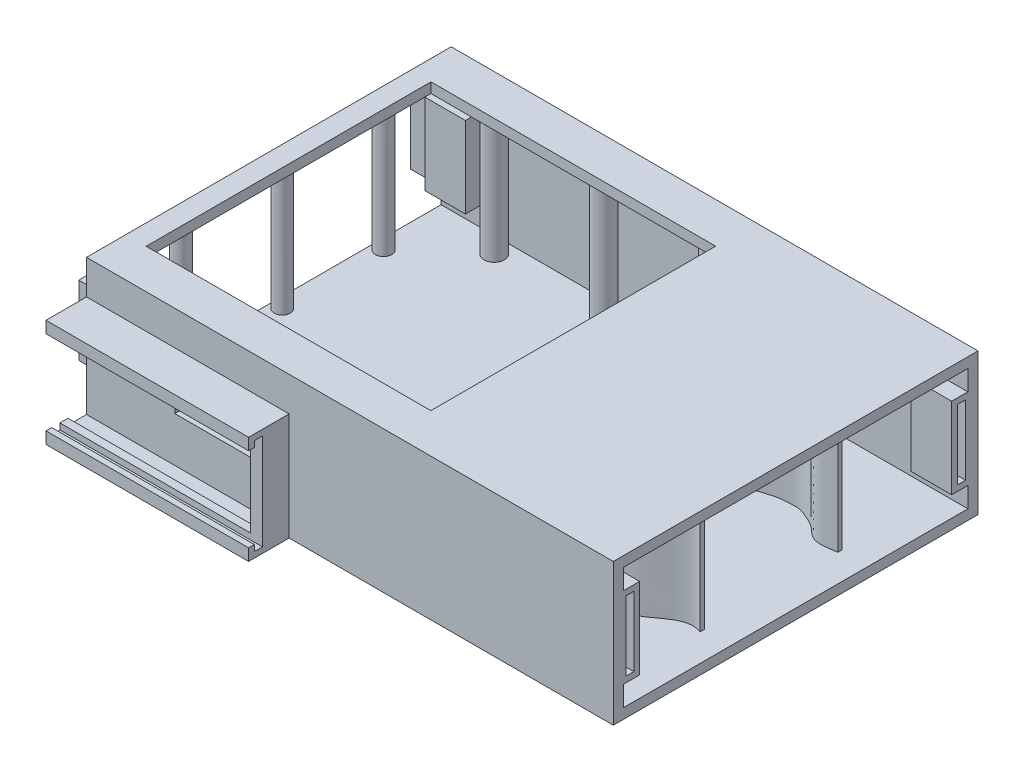
SolidWorks part; units mm, degrees
ref_plane "Спереди" through (0, 0, 0) normal (0, 0, 1) x (1, 0, 0)
ref_plane "Сверху" through (0, 0, 0) normal (0, 1, 0) x (1, 0, 0)
ref_plane "Справа" through (0, 0, 0) normal (1, 0, 0) x (0, 0, -1)
sketch "Эскиз1" plane through (0, 0, 0) normal (0, 1, 0) x (1, 0, 0)
  line L1 (-94.2008, -43.9132) -> (35.7992, -43.9132)
  line L2 (-94.2008, -43.9132) -> (-94.2008, 46.0868)
  line L3 (-94.2008, 46.0868) -> (35.7992, 46.0868)
  line L4 (35.7992, -43.9132) -> (35.7992, 46.0868)
  point P0 (0, 0)
extrude "Бобышка-Вытянуть1" add sketch "Эскиз1" along normal blind 35
sketch "Эскиз2" plane through (-94.2008, 0, 0) normal (-1, 0, 0) x (0, 0, 1)
  line L0 (-1046.0868, 17.5) -> (48953.9132, 17.5) construction
  line L1 (-46.0868, 35) -> (-46.0868, 0) construction
  line L2 (-1.0868, -965) -> (-1.0868, 49035) construction
  line L3 (-46.0868, 35) -> (43.9132, 35) construction
  line L5 (-43.5868, 2.5) -> (41.4132, 2.5)
  line L6 (-43.5868, 2.5) -> (-43.5868, 32.5)
  line L7 (-43.5868, 32.5) -> (41.4132, 32.5)
  line L8 (41.4132, 2.5) -> (41.4132, 32.5)
  line L9 (-43.5868, 2.5) -> (41.4132, 32.5) construction
  line L10 (-43.5868, 32.5) -> (41.4132, 2.5) construction
  point P5 (-46.0868, 17.5)
  point P6 (-1.0868, 17.5)
  point P10 (-1.0868, 35)
extrude "Вырез-Вытянуть1" cut sketch "Эскиз2" against normal through all
sketch "Эскиз3" plane through (-94.2008, 0, 0) normal (-1, 0, 0) x (0, 0, 1)
  line L0 (-43.5868, 27.5) -> (-43.5868, 7.5)
  line L1 (-43.5868, 32.5) -> (-43.5868, 2.5) construction
  line L2 (37.4132, 27.5) -> (37.4132, 7.5)
  line L3 (-43.5868, 7.5) -> (-39.5868, 7.5)
  line L4 (-39.5868, 7.5) -> (-39.5868, 27.5)
  line L5 (-39.5868, 27.5) -> (-43.5868, 27.5)
  line L6 (37.4132, 7.5) -> (41.4132, 7.5)
  line L7 (41.4132, 7.5) -> (41.4132, 27.5)
  line L8 (41.4132, 27.5) -> (37.4132, 27.5)
  dimension "D1" = 2
extrude "Бобышка-Вытянуть2" add sketch "Эскиз3" against normal blind 10
sketch "Эскиз4" plane through (-94.2008, 0, 0) normal (-1, 0, 0) x (0, 0, 1)
  line L6 (-41.0011, 8.9142) -> (-41.0011, 26.0858)
  line L7 (38.8274, 8.9142) -> (38.8274, 26.0858)
  line L8 (-41.0011, 26.0858) -> (-43.0011, 26.0858)
  line L9 (38.8274, 26.0858) -> (40.8274, 26.0858)
  line L10 (-43.0011, 26.0858) -> (-43.0011, 8.9142)
  line L11 (40.8274, 26.0858) -> (40.8274, 8.9142)
  line L12 (-43.0011, 8.9142) -> (-41.0011, 8.9142)
  line L13 (40.8274, 8.9142) -> (38.8274, 8.9142)
extrude "Бобышка-Вытянуть3" add sketch "Эскиз4" along normal blind 5
sketch "Эскиз5" plane through (0, 0, 43.9132) normal (0, 0, 1) x (1, 0, 0)
  line L3 (-72.421, 12.5) -> (-52.421, 12.5)
  line L4 (-72.421, 12.5) -> (-72.421, 22.5)
  line L5 (-72.421, 22.5) -> (-52.421, 22.5)
  line L6 (-52.421, 12.5) -> (-52.421, 22.5)
  line L7 (-72.421, 12.5) -> (-52.421, 22.5) construction
  line L8 (-72.421, 22.5) -> (-52.421, 12.5) construction
  point P1 (-62.421, 17.5)
extrude "Вырез-Вытянуть2" cut sketch "Эскиз5" against normal blind 5
sketch "Эскиз6" plane through (-94.2008, 0, 0) normal (-1, 0, 0) x (0, 0, 1)
  line L1 (43.9132, 35) -> (43.9132, 0) construction
  line L2 (43.9132, 26.54) -> (53.9132, 26.54)
  line L3 (53.9132, 26.54) -> (53.9132, 0)
  line L4 (53.9132, 0) -> (43.9132, 0)
  line L5 (43.9132, 0) -> (43.9132, 26.54)
extrude "Бобышка-Вытянуть4" add sketch "Эскиз6" against normal blind 50
sketch "Эскиз7" plane through (-94.2008, 0, 0) normal (-1, 0, 0) x (0, 0, 1)
  line L2 (52.4989, 25.1258) -> (52.4989, 1.4142)
  line L4 (52.4989, 25.1258) -> (43.9132, 25.1258)
  line L5 (43.9132, 25.1258) -> (43.9132, 1.4142)
  line L6 (43.9132, 1.4142) -> (52.4989, 1.4142)
extrude "Вырез-Вытянуть3" cut sketch "Эскиз7" against normal blind 47
sketch "Эскиз8" plane through (-94.2008, 0, 0) normal (-1, 0, 0) x (0, 0, 1)
  line L1 (53.9132, 0) -> (53.9132, 26.54) construction
  line L3 (53.9132, 2.91) -> (51.6765, 2.91)
  line L4 (51.6765, 2.91) -> (51.6765, 23.66)
  line L5 (51.6765, 23.66) -> (58.0156, 23.66)
  line L6 (58.0156, 23.66) -> (58.0156, 2.91)
  line L7 (58.0156, 2.91) -> (53.9132, 2.91)
extrude "Вырез-Вытянуть4" cut sketch "Эскиз8" against normal through all
sketch "Эскиз9" plane through (-94.2008, 0, 0) normal (-1, 0, 0) x (0, 0, 1)
  line L1 (52.4989, 25.1258) -> (43.9132, 25.1258) construction
  line L2 (43.9132, 1.4142) -> (52.4989, 1.4142) construction
  line L3 (50.4989, 25.1258) -> (50.4989, 23.66)
  line L4 (50.4989, 23.66) -> (48.5003, 23.66)
  line L5 (48.5003, 23.66) -> (48.5003, 25.1258)
  line L6 (48.5003, 25.1258) -> (50.4989, 25.1258)
  line L7 (50.4989, 1.4142) -> (50.4989, 2.91)
  line L8 (50.4989, 2.91) -> (48.5003, 2.91)
  line L9 (48.5003, 2.91) -> (48.5003, 1.4142)
  line L10 (48.5003, 1.4142) -> (50.4989, 1.4142)
extrude "Бобышка-Вытянуть5" add sketch "Эскиз9" against normal blind 47
sketch "Эскиз10" plane through (-47.2008, 0, 0) normal (-1, 0, 0) x (0, 0, 1)
  line L1 (52.4989, 23.66) -> (52.4989, 25.1258)
  line L2 (52.4989, 25.1258) -> (50.4989, 25.1258)
  line L3 (50.4989, 25.1258) -> (50.4989, 23.66)
  line L5 (51.6765, 2.91) -> (52.4989, 2.91) construction
  line L6 (52.4989, 2.91) -> (52.4989, 1.4142)
  line L7 (52.4989, 1.4142) -> (50.4989, 1.4142)
  line L8 (50.4989, 1.4142) -> (50.4989, 2.91)
  line L9 (50.4989, 2.91) -> (50.4989, 23.66)
  line L10 (52.4989, 23.66) -> (52.4989, 2.91)
extrude "Вырез-Вытянуть5" cut sketch "Эскиз10" along normal through all and the other way through all
sketch "Эскиз11" plane through (0, 35, 0) normal (0, 1, 0) x (1, 0, 0)
  line L4 (-89.2008, 36.0868) -> (-18.9542, 36.0868)
  line L5 (-89.2008, 36.0868) -> (-89.2008, -34.1906)
  line L6 (-89.2008, -34.1906) -> (-18.9542, -34.1906)
  line L7 (-18.9542, 36.0868) -> (-18.9542, -34.1906)
extrude "Вырез-Вытянуть6" cut sketch "Эскиз11" against normal blind 10
pattern_linear "Линейный массив1" count 2 spacing 120 along (1, 0, 0) of "Бобышка-Вытянуть2"
sketch "Эскиз12" plane through (35.7992, 0, 0) normal (1, 0, 0) x (0, 0, -1)
  line L1 (41.0011, 26.0858) -> (41.0011, 8.9142)
  line L2 (41.0011, 8.9142) -> (43.0011, 8.9142)
  line L3 (-38.8274, 26.0858) -> (-40.8274, 26.0858)
  line L5 (-40.8274, 26.0858) -> (-40.8274, 8.9142)
  line L7 (-40.8274, 8.9142) -> (-38.8274, 8.9142)
  line L9 (-38.8274, 26.0858) -> (-38.8274, 8.9142)
  line L11 (43.0011, 8.9142) -> (43.0011, 26.0858)
  line L12 (43.0011, 26.0858) -> (41.0011, 26.0858)
extrude "Вырез-Вытянуть7" cut sketch "Эскиз12" against normal blind 5
sketch "Эскиз13" plane through (0, 2.5, 0) normal (0, 1, 0) x (1, 0, 0)
  line L4 (-5.6855, 20.5799) -> (-5.5186, 18.2705)
  line L6 (-5.6855, -16.9659) -> (-5.5186, -14.6565)
  line L7 (29.0476, 19.3345) -> (29.0476, 18.2705)
  line L8 (29.0476, -15.7205) -> (29.0476, -14.6565)
  circle A0 centre (-91.619, 26.807) radius 2
  circle A1 centre (-91.619, 1.807) radius 2
  circle A2 centre (-91.619, -23.193) radius 2
  circle A3 centre (-77.0892, 39.5868) radius 2.5
  circle A4 centre (-50.0892, 39.5868) radius 2.5
  circle A5 centre (-23.0892, 39.5868) radius 2.5
  circle A6 centre (-77.0892, -37.4132) radius 2.5
  circle A7 centre (-50.0892, -37.4132) radius 2.5
  circle A8 centre (-23.0892, -37.4132) radius 2.5
  circle A9 centre (-13.4348, 26.807) radius 2.5
  circle A10 centre (-13.4348, 1.807) radius 2.5
  circle A11 centre (-13.4348, -23.193) radius 2.5
  spline S0 degree 3 poles (-5.6855, 20.5799) (-2.6664, 18.468) (2.5603, 21.5488) (9.7498, 24.1679) (19.6278, 25.1699) (23.8277, 17.6011) (29.0476, 19.3345) knots 0 0 0 0 0.25429 0.449975 0.646169 1 1 1 1
  spline S1 degree 3 poles (-5.6855, -16.9659) (-2.6664, -14.854) (2.5603, -17.9348) (9.7498, -20.5539) (19.6278, -21.5559) (23.8277, -13.9871) (29.0476, -15.7205) knots 0 0 0 0 0.25429 0.449975 0.646169 1 1 1 1
  spline S2 degree 3 poles (-5.5186, 18.2705) (-4.9776, 19.2636) (-3.5952, 18.4498) (-1.689, 18.149) (0.0421, 18.8083) (2.0071, 19.623) (3.9618, 20.5603) (5.9946, 21.4088) (8.1252, 22.0974) (10.1474, 22.6295) (12.3639, 22.7072) (14.5238, 23.0128) (16.6244, 22.2834) (18.4134, 21.5307) (20.0844, 20.6666) (21.4518, 19.3342) (24.081, 17.2282) (27.1877, 18.0095) (29.0476, 18.2705) knots 0 0 0 0 0.070419 0.103339 0.158232 0.214989 0.278149 0.33389 0.393968 0.460317 0.502538 0.574388 0.634142 0.679587 0.733137 0.785087 0.834959 1 1 1 1
  spline S3 degree 3 poles (-5.5186, -14.6565) (-4.9776, -15.6496) (-3.5952, -14.8358) (-1.689, -14.535) (0.0421, -15.1943) (2.0071, -16.0089) (3.9618, -16.9463) (5.9946, -17.7948) (8.1252, -18.4834) (10.1474, -19.0155) (12.3639, -19.0932) (14.5238, -19.3988) (16.6244, -18.6694) (18.4134, -17.9167) (20.0844, -17.0526) (21.4518, -15.7202) (24.081, -13.6142) (27.1877, -14.3955) (29.0476, -14.6565) knots 0 0 0 0 0.070419 0.103339 0.158232 0.214989 0.278149 0.33389 0.393968 0.460317 0.502538 0.574388 0.634142 0.679587 0.733137 0.785087 0.834959 1 1 1 1
  point P46 (26.3121, 18.0777)
  point P55 (8.0712, 21.8318)
  point P57 (4.0521, 20.5799)
  point P59 (26.7305, -14.3072)
  point P61 (5.9544, -17.7485)
  point P63 (8.0603, -18.4419)
  point P65 (10.4486, -18.9812)
  dimension "D1" = 3
  dimension "D2" = 3
  dimension "D3" = 3
  dimension "D4" = 3
extrude "Бобышка-Вытянуть6" add sketch "Эскиз13" along normal blind 32
